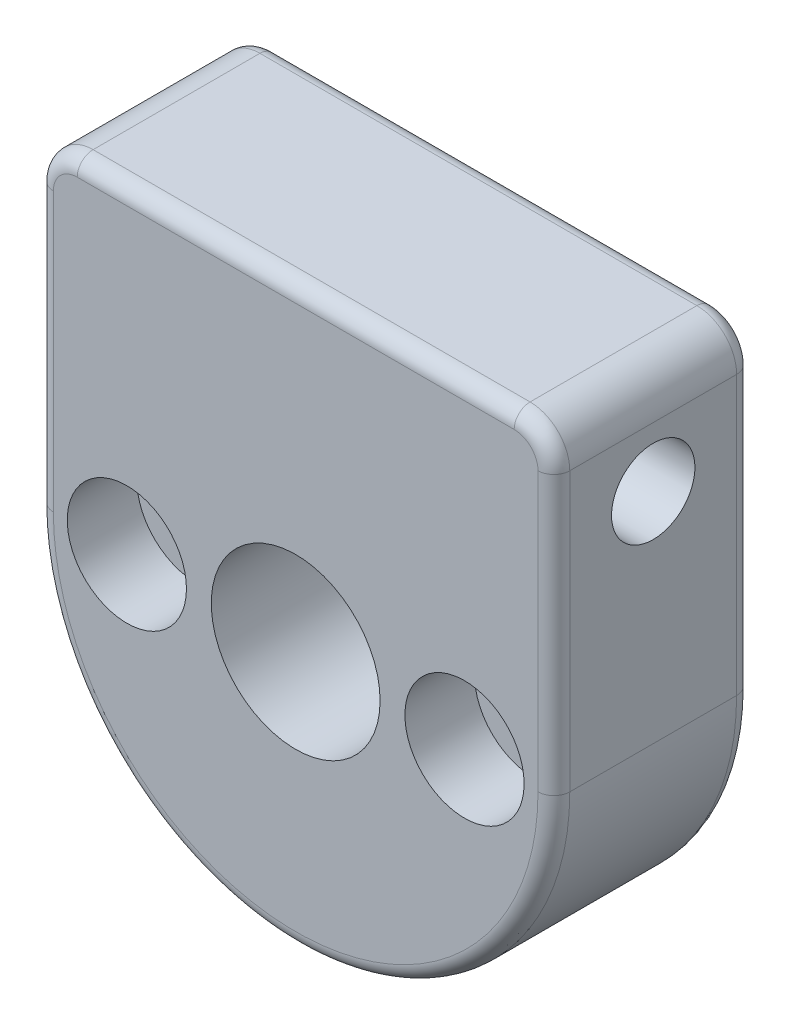
SolidWorks part; units mm, degrees
material "ABS"
ref_plane "Front" through (0, 0, 0) normal (0, 0, 1) x (1, 0, 0)
ref_plane "Top" through (0, 0, 0) normal (0, 1, 0) x (1, 0, 0)
ref_plane "Right" through (0, 0, 0) normal (1, 0, 0) x (0, 0, -1)
sketch "Esquisse1" plane through (0, 0, 0) normal (0, 0, 1) x (1, 0, 0)
  line L0 (0, -50) -> (0, 50) construction
  line L1 (-13, 16) -> (13, 16)
  line L2 (-13, 16) -> (-13, 0)
  line L3 (-13, 0) -> (13, 0) construction
  line L4 (13, 16) -> (13, 0)
  arc A0 (-13, 0) -> (13, 0) centre (0, 0) ccw
  circle A1 centre (-8.5, 0) radius 1.6
  circle A2 centre (8.5, 0) radius 1.6
  circle A3 centre (0, 0) radius 4.25
  dimension "D1" = 3.2
  dimension "D2" = 13
  dimension "D3" = 17
  dimension "D5" = 8.5
  dimension "D4" = 16
extrude "Boss.-Extru.1" add sketch "Esquisse1" along normal blind 10
sketch "Esquisse2" plane through (0, 0, 10) normal (0, 0, 1) x (1, 0, 0)
  circle A0 centre (-8.5, 0) radius 3
  circle A1 centre (8.5, 0) radius 3
  dimension "D1" = 6
extrude "Enlèv. mat.-Extru.1" cut sketch "Esquisse2" against normal blind 3.5
sketch "Esquisse3" plane through (-13, 0, 0) normal (-1, 0, 0) x (0, 0, 1)
  line L0 (10, 16) -> (0, 16) construction
  circle A0 centre (5, 11) radius 2.1
  point P4 (5, 16)
  dimension "D1" = 4.2
  dimension "D2" = 5
extrude "Enlèv. mat.-Extru.2" cut sketch "Esquisse3" against normal through all
fillet "Congé1" radius 2 2 edges at (13, 16, 5) (-13, 16, 5)
fillet "Congé2" radius 0.8 12 edges at (0, -13, 0) (-13, 7, 0) (-12.4142, 15.4142, 0) (0, 16, 0) (12.4142, 15.4142, 0) (0, -13, 10) (-13, 7, 10) (-12.4142, 15.4142, 10) (0, 16, 10) (12.4142, 15.4142, 10) (13, 7, 0) (13, 7, 10)
